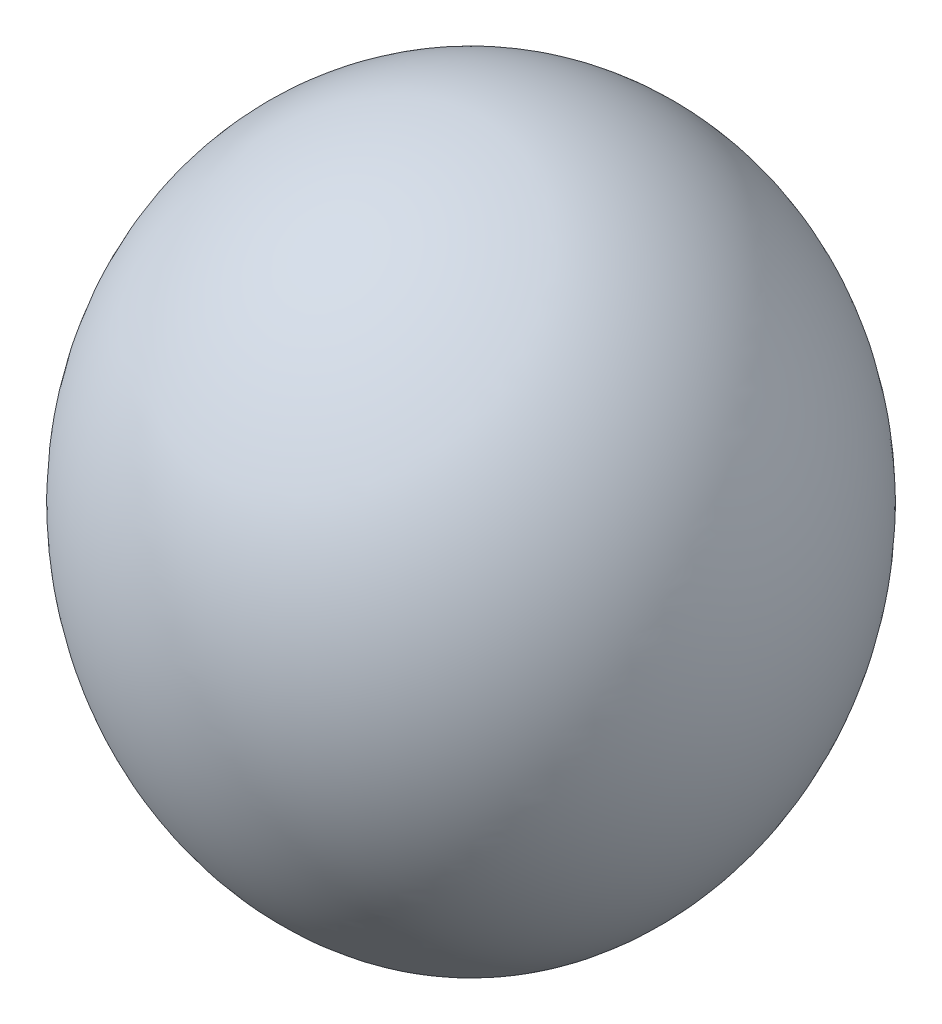
SolidWorks part; units mm, degrees
ref_plane "Front Plane" through (0, 0, 0) normal (0, 0, 1) x (1, 0, 0)
ref_plane "Top Plane" through (0, 0, 0) normal (0, 1, 0) x (1, 0, 0)
ref_plane "Right Plane" through (0, 0, 0) normal (1, 0, 0) x (0, 0, -1)
sketch "Sketch1" plane through (0, 0, 0) normal (0, 0, 1) x (1, 0, 0)
  line L0 (0, 318.3099) -> (0, -79.5775) construction
  line L1 (0, 0) -> (0, 318.3099)
  spline S0 degree 4 poles (0, 0) (0.0859, -0.0283) (0.2587, -0.0818) (0.608, -0.1768) (1.1365, -0.3007) (1.7574, -0.4255) (2.4709, -0.5464) (3.1873, -0.6492) (3.9058, -0.7357) (4.6259, -0.8076) (5.7666, -0.9) (7.33, -0.9784) (9.3162, -1.0015) (11.722, -0.9256) (14.3972, -0.7379) (17.3359, -0.412) (20.5304, 0.0772) (23.9708, 0.754) (28.2348, 1.7676) (33.2873, 3.2325) (39.078, 5.2693) (45.5398, 7.9988) (53.1168, 11.7234) (61.6611, 16.6752) (74.1381, 25.2582) (89.4923, 38.7566) (105.3345, 57.2109) (120.0296, 81.2295) (130.8438, 107.2218) (137.5707, 134.5581) (140.0255, 162.6059) (138.301, 187.187) (133.992, 207.8306) (128.5068, 224.4988) (122.9865, 237.4068) (116.3472, 249.7776) (109.5792, 260.0311) (103.1158, 268.3378) (96.1414, 276.2133) (88.6704, 283.6275) (79.6712, 291.1982) (69.8927, 297.9354) (61.1222, 302.9706) (54.4053, 306.2595) (49.4752, 308.4023) (45.3967, 310.005) (42.1008, 311.1994) (38.7739, 312.3047) (35.4184, 313.3198) (32.0367, 314.2438) (28.6311, 315.0756) (25.2041, 315.8143) (21.7582, 316.4593) (18.2961, 317.0097) (15.2543, 317.4081) (12.6407, 317.6899) (10.4579, 317.8848) (8.7115, 318.0167) (7.0172, 318.121) (5.3862, 318.2002) (3.99, 318.25) (2.8616, 318.2796) (1.8884, 318.2966) (1.1751, 318.3057) (0.2454, 318.3106) (-0.4294, 318.3101) (-1.5257, 318.3031) (-2.3994, 318.2882) (-3.6658, 318.2604) (-5.0925, 318.2121) (-6.8125, 318.1341) (-8.7425, 318.0154) (-10.6884, 317.867) (-12.6222, 317.689) (-15.0414, 317.4297) (-17.9349, 317.0596) (-22.2619, 316.3946) (-27.0517, 315.4583) (-31.8162, 314.325) (-36.5452, 312.9956) (-40.3193, 311.8093) (-43.1214, 310.8339) (-44.9759, 310.1462) (-45.8995, 309.793) knots 0 0 0 0 0 0.000701 0.001401 0.002803 0.004204 0.005605 0.007007 0.008408 0.00981 0.011211 0.015871 0.020531 0.025191 0.029851 0.036639 0.043428 0.050216 0.057005 0.070581 0.084157 0.097734 0.11131 0.135947 0.160585 0.21489 0.269195 0.3235 0.377805 0.43211 0.486414 0.540719 0.567872 0.595024 0.622177 0.649329 0.676482 0.690058 0.703634 0.730787 0.757939 0.781003 0.795479 0.809056 0.815844 0.822632 0.82942 0.836208 0.842996 0.849784 0.856572 0.86336 0.870149 0.876937 0.883725 0.887119 0.890513 0.893907 0.897301 0.900249 0.903196 0.90467 0.906143 0.907617 0.909091 0.910974 0.912858 0.914741 0.916625 0.920391 0.924158 0.927925 0.931692 0.935459 0.939226 0.946759 0.954293 0.96936 0.97702 0.98468 0.99234 1 1 1 1 1 construction
  spline S1 degree 4 poles (0, 0) (0.0859, -0.0283) (0.2587, -0.0818) (0.608, -0.1768) (1.1365, -0.3007) (1.7574, -0.4255) (2.4709, -0.5464) (3.1873, -0.6492) (3.9058, -0.7357) (4.6259, -0.8076) (5.7666, -0.9) (7.33, -0.9784) (9.3162, -1.0015) (11.722, -0.9256) (14.3972, -0.7379) (17.3359, -0.412) (20.5304, 0.0772) (23.9708, 0.754) (28.2348, 1.7676) (33.2873, 3.2325) (39.078, 5.2693) (45.5398, 7.9988) (53.1168, 11.7234) (61.6611, 16.6752) (74.1381, 25.2582) (89.4923, 38.7566) (105.3345, 57.2109) (120.0296, 81.2295) (130.8438, 107.2218) (137.5707, 134.5581) (140.0255, 162.6059) (138.301, 187.187) (133.992, 207.8306) (128.5068, 224.4988) (122.9865, 237.4068) (116.3472, 249.7776) (109.5792, 260.0311) (103.1158, 268.3378) (96.1414, 276.2133) (88.6704, 283.6275) (79.6712, 291.1982) (69.8927, 297.9354) (61.1222, 302.9706) (54.4053, 306.2595) (49.4752, 308.4023) (45.3967, 310.005) (42.1008, 311.1994) (38.7739, 312.3047) (35.4184, 313.3198) (32.0367, 314.2438) (28.6311, 315.0756) (25.2041, 315.8143) (21.7582, 316.4593) (18.2961, 317.0097) (15.2543, 317.4081) (12.6407, 317.6899) (10.4579, 317.8848) (8.7115, 318.0167) (7.0172, 318.121) (5.3862, 318.2002) (3.99, 318.25) (2.8616, 318.2796) (1.8884, 318.2966) (1.1751, 318.3057) (0.5231, 318.3091) (0.173, 318.3099) (0, 318.3099) knots 0 0 0 0 0 0.000701 0.001401 0.002803 0.004204 0.005605 0.007007 0.008408 0.00981 0.011211 0.015871 0.020531 0.025191 0.029851 0.036639 0.043428 0.050216 0.057005 0.070581 0.084157 0.097734 0.11131 0.135947 0.160585 0.21489 0.269195 0.3235 0.377805 0.43211 0.486414 0.540719 0.567872 0.595024 0.622177 0.649329 0.676482 0.690058 0.703634 0.730787 0.757939 0.781003 0.795479 0.809056 0.815844 0.822632 0.82942 0.836208 0.842996 0.849784 0.856572 0.86336 0.870149 0.876937 0.883725 0.887119 0.890513 0.893907 0.897301 0.900249 0.903196 0.90467 0.906143 0.907617 0.909091 0.909091 0.909091 0.909091 0.909091
revolve "Revolve1" add sketch "Sketch1" angle 360 about L0
